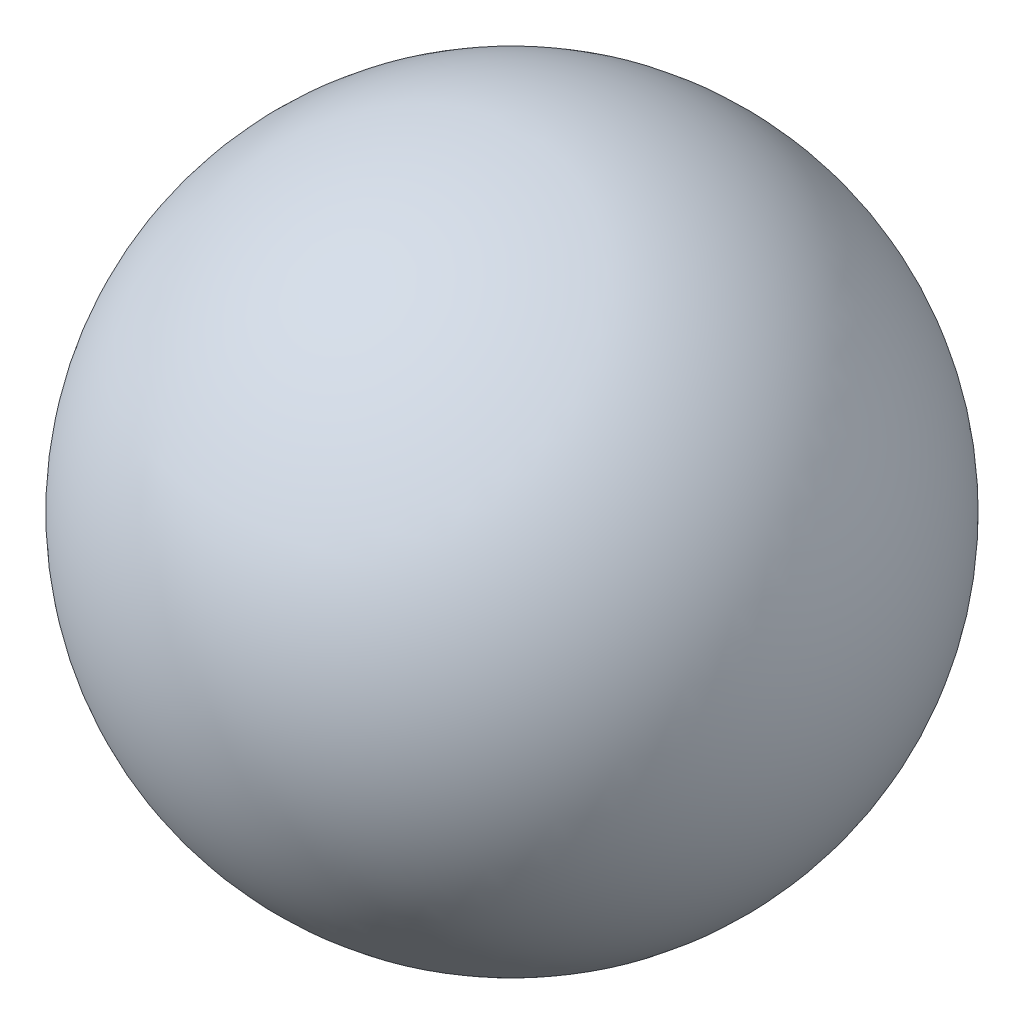
SolidWorks part; units mm, degrees
ref_plane "Piano frontale" through (0, 0, 0) normal (0, 0, 1) x (1, 0, 0)
ref_plane "Piano superiore" through (0, 0, 0) normal (0, 1, 0) x (1, 0, 0)
ref_plane "Piano destro" through (0, 0, 0) normal (1, 0, 0) x (0, 0, -1)
sketch "Schizzo1" plane through (0, 0, 0) normal (0, 0, 1) x (1, 0, 0)
  line L0 (0, 0) -> (0, 120)
  arc A0 (0, 120) -> (0, 0) centre (0, 60) ccw
  dimension "D1" = 60
revolve "Rivoluzione1" add sketch "Schizzo1" angle 360 about L0
